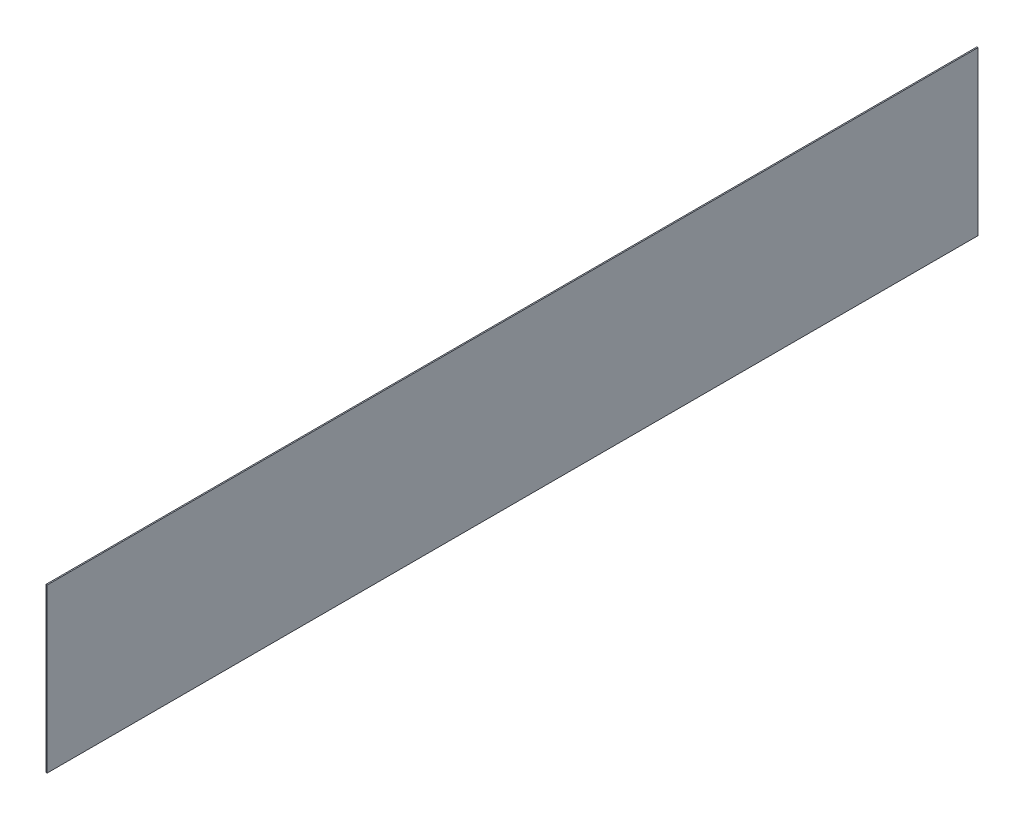
SolidWorks part; units mm, degrees
ref_plane "Front Plane" through (0, 0, 0) normal (0, 0, 1) x (1, 0, 0)
ref_plane "Top Plane" through (0, 0, 0) normal (0, 1, 0) x (1, 0, 0)
ref_plane "Right Plane" through (0, 0, 0) normal (1, 0, 0) x (0, 0, -1)
sketch "Sketch1" plane through (0, 0, 0) normal (1, 0, 0) x (0, 0, -1)
  line L1 (-4000, 700) -> (4000, 700)
  line L2 (-4000, 700) -> (-4000, -700)
  line L3 (-4000, -700) -> (4000, -700)
  line L4 (4000, 700) -> (4000, -700)
  line L5 (-4000, 700) -> (4000, -700) construction
  line L6 (-4000, -700) -> (4000, 700) construction
  point P0 (0, 0)
  dimension "D1" = 8000
  dimension "D2" = 1400
extrude "Boss-Extrude1" add sketch "Sketch1" along normal blind 10
